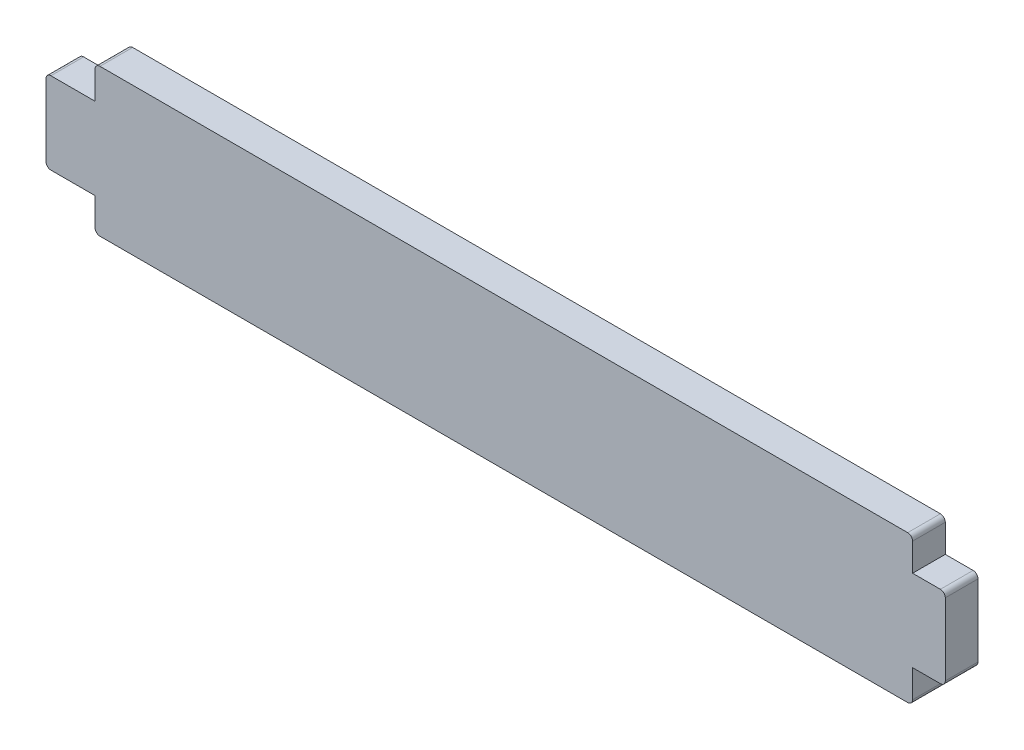
SolidWorks part; units mm, degrees
ref_plane "Ön Düzlem" through (0, 0, 0) normal (0, 0, 1) x (1, 0, 0)
ref_plane "Üst Düzlem" through (0, 0, 0) normal (0, 1, 0) x (1, 0, 0)
ref_plane "Sağ Düzlem" through (0, 0, 0) normal (1, 0, 0) x (0, 0, -1)
sketch "Sketch1" plane through (0, 0, 0) normal (0, 0, 1) x (1, 0, 0)
  line L1 (-27.5, -4.5) -> (27.5, -4.5)
  line L2 (-27.5, -4.5) -> (-27.5, 4.5)
  line L3 (-27.5, 4.5) -> (27.5, 4.5)
  line L4 (27.5, -4.5) -> (27.5, 4.5)
  line L5 (-27.5, -4.5) -> (27.5, 4.5) construction
  line L6 (-27.5, 4.5) -> (27.5, -4.5) construction
  line L7 (-27.5, 4.5) -> (-24.5, 4.5)
  line L8 (-27.5, 4.5) -> (-27.5, 2.5)
  line L9 (-27.5, 2.5) -> (-24.5, 2.5)
  line L10 (-24.5, 4.5) -> (-24.5, 2.5)
  line L11 (-27.5, -4.5) -> (-24.5, -4.5)
  line L12 (-27.5, -4.5) -> (-27.5, -2.5)
  line L13 (-27.5, -2.5) -> (-24.5, -2.5)
  line L14 (-24.5, -4.5) -> (-24.5, -2.5)
  line L15 (27.5, 4.5) -> (25.5, 4.5)
  line L16 (27.5, 4.5) -> (27.5, 2.5)
  line L17 (27.5, 2.5) -> (25.5, 2.5)
  line L18 (25.5, 4.5) -> (25.5, 2.5)
  line L19 (27.5, -4.5) -> (25.5, -4.5)
  line L20 (27.5, -4.5) -> (27.5, -2.5)
  line L21 (27.5, -2.5) -> (25.5, -2.5)
  line L22 (25.5, -4.5) -> (25.5, -2.5)
  point P0 (0, 0)
  dimension "D1" = 9
  dimension "D2" = 55
  dimension "D3" = 2
  dimension "D4" = 2
  dimension "D5" = 3
  dimension "D6" = 3
  dimension "D7" = 2
  dimension "D8" = 2
extrude "Boss-Extrude1" add sketch "Sketch1" along normal blind 2 contours L1 L22 L21 L4 L17 L18 L3 L10 L9 L2 L13 L14
fillet "Fillet5" radius 0.3 1 edges at (-27.5, -2.5, 1)
fillet "Fillet7" radius 0.3 1 edges at (-24.5, -4.5, 1)
fillet "Fillet8" radius 0.3 1 edges at (-24.5, 4.5, 1)
fillet "Fillet9" radius 0.3 1 edges at (25.5, -4.5, 1)
fillet "Fillet10" radius 0.3 3 edges at (25.5, 4.5, 1) (27.5, 2.5, 1) (27.5, -2.5, 1)
fillet "Fillet11" radius 0.3 1 edges at (-27.5, 2.5, 1)
